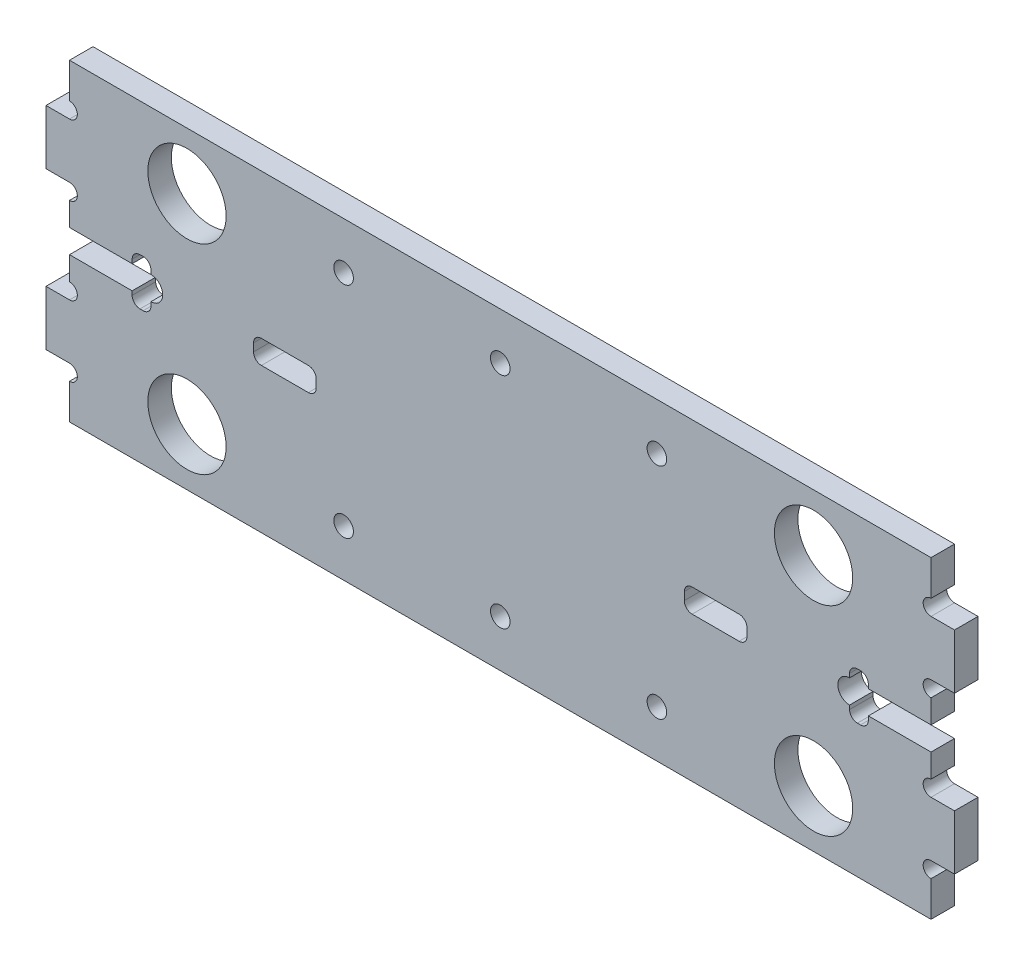
SolidWorks part; units mm, degrees
material "Acrylic (Medium-high impact)"
ref_plane "Front Plane" through (0, 0, 0) normal (0, 0, 1) x (1, 0, 0)
ref_plane "Top Plane" through (0, 0, 0) normal (0, 1, 0) x (1, 0, 0)
ref_plane "Right Plane" through (0, 0, 0) normal (1, 0, 0) x (0, 0, -1)
sketch "Sketch1" plane through (0, 0, 0) normal (0, 0, 1) x (1, 0, 0)
  line L0 (0, 20) -> (0, -20) construction
  line L1 (-55, 20) -> (55, 20)
  line L2 (-55, 20) -> (-55, -20)
  line L3 (-55, -20) -> (55, -20)
  line L4 (55, 20) -> (55, -20)
  line L5 (55, 0) -> (-55, 0) construction
  point P8 (0, 0)
extrude "Boss-Extrude1" add sketch "Sketch1" along normal blind 3
sketch "Sketch2" plane through (0, 0, 3) normal (0, 0, 1) x (1, 0, 0)
  line L0 (-55, 0) -> (55, 0) construction
  line L1 (-55, 20) -> (-55, -20) construction
  line L2 (55, -20) -> (55, 20) construction
  line L3 (55, 0) -> (55, -20) construction
  line L4 (55, 0) -> (55, 20) construction
  line L5 (55, 20) -> (58, 20) construction
  line L6 (58, 20) -> (58, -20) construction
  line L7 (58, -20) -> (55, -20) construction
  line L8 (0, 20) -> (0, -20) construction
  line L9 (55, 20) -> (-55, 20) construction
  line L10 (-55, -20) -> (55, -20) construction
  line L11 (55, -10) -> (58, -10) construction
  line L12 (55, 10) -> (58, 10) construction
  line L13 (58, 10) -> (58, 13.5)
  line L14 (58, 10) -> (58, 6.5)
  line L15 (58, 6.5) -> (55, 6.5)
  line L16 (55, 6.5) -> (55, 13.5)
  line L17 (55, 13.5) -> (58, 13.5)
  line L18 (55, -10) -> (55, -6.5)
  line L19 (55, -6.5) -> (58, -6.5)
  line L20 (58, -6.5) -> (58, -13.5)
  line L21 (58, -13.5) -> (55, -13.5)
  line L22 (55, -13.5) -> (55, -10)
  line L23 (-55, 6.5) -> (-55, 13.5)
  line L24 (-55, -13.5) -> (-55, -10)
  line L25 (-55, -10) -> (-55, -6.5)
  line L26 (-55, 10) -> (-58, 10) construction
  line L27 (-55, -10) -> (-58, -10) construction
  line L28 (-58, -20) -> (-55, -20) construction
  line L29 (-58, 20) -> (-58, -20) construction
  line L30 (-55, 20) -> (-58, 20) construction
  line L31 (-58, -13.5) -> (-55, -13.5)
  line L32 (-58, -6.5) -> (-58, -13.5)
  line L33 (-55, -6.5) -> (-58, -6.5)
  line L34 (-55, 13.5) -> (-58, 13.5)
  line L35 (-58, 6.5) -> (-55, 6.5)
  line L36 (-58, 10) -> (-58, 6.5)
  line L37 (-58, 10) -> (-58, 13.5)
extrude "Boss-Extrude2" add sketch "Sketch2" against normal blind 3
sketch "Sketch3" plane through (0, 0, 3) normal (0, 0, 1) x (1, 0, 0)
  line L0 (-55, 0) -> (55, 0) construction
  line L1 (-55, 6.5) -> (-55, -6.5) construction
  line L2 (55, -6.5) -> (55, 6.5) construction
  line L3 (-55, 13.5) -> (-55, 14.5) construction
  line L4 (-55, 20) -> (-55, 13.5) construction
  line L5 (-55, 14.5) -> (55, 14.5) construction
  line L6 (55, 13.5) -> (55, 20) construction
  line L7 (55, 14.5) -> (55, 5.5) construction
  line L8 (55, 5.5) -> (-55, 5.5) construction
  line L9 (-55, -6.5) -> (-55, -5.5) construction
  line L10 (-55, -5.5) -> (55, -5.5) construction
  line L11 (55, -5.5) -> (55, -14.5) construction
  line L12 (55, -20) -> (55, -13.5) construction
  line L13 (55, -14.5) -> (-55, -14.5) construction
  line L14 (-55, -13.5) -> (-55, -20) construction
  circle A1 centre (-55, 14.5) radius 1
  circle A2 centre (-55, 5.5) radius 1
  circle A3 centre (-55, -5.5) radius 1
  circle A4 centre (-55, -14.5) radius 1
  circle A5 centre (55, 14.5) radius 1
  circle A6 centre (55, 5.5) radius 1
  circle A7 centre (55, -5.5) radius 1
  circle A8 centre (55, -14.5) radius 1
extrude "Cut-Extrude1" cut sketch "Sketch3" against normal blind 3
sketch "Sketch4" plane through (0, 0, 3) normal (0, 0, 1) x (1, 0, 0)
  line L0 (-55, 0) -> (55, 0) construction
  line L1 (-55, 4.5) -> (-55, -4.5) construction
  line L2 (55, -4.5) -> (55, 4.5) construction
  line L3 (55, 0) -> (55, -1.5) construction
  line L4 (55, -1.5) -> (-55, -1.5) construction
  line L5 (-55, -1.5) -> (-55, 1.5) construction
  line L6 (-55, 1.5) -> (55, 1.5) construction
  line L7 (55, 1.5) -> (47, 1.5) construction
  line L8 (47, 20) -> (47, -20) construction
  line L9 (55, 20) -> (-55, 20) construction
  line L10 (-55, -20) -> (55, -20) construction
  line L11 (-55, 1.5) -> (-47, 1.5) construction
  line L12 (-47, 20) -> (-47, -20) construction
  line L13 (-47, 20) -> (-44.6, 20) construction
  line L14 (-44.6, 20) -> (-44.6, -20) construction
  line L15 (47, 20) -> (44.6, 20) construction
  line L16 (44.6, 20) -> (44.6, -20) construction
  line L17 (55, 1.5) -> (55, 3) construction
  line L18 (55, 3) -> (-55, 3) construction
  line L19 (-55, 3) -> (-55, -3) construction
  line L20 (-55, -3) -> (55, -3) construction
  line L21 (-44.6, 0) -> (-43.1, 0) construction
  line L22 (44.6, 0) -> (43.1, 0) construction
  line L24 (-55, 1.5) -> (-47, 1.5)
  line L25 (-55, 1.5) -> (-55, -1.5)
  line L26 (-55, -1.5) -> (-47, -1.5)
  line L27 (-47, 1.5) -> (-47, -1.5)
  line L28 (-47, 3) -> (-44.6, 3)
  line L29 (-47, 3) -> (-47, -3)
  line L30 (-47, -3) -> (-44.6, -3)
  line L31 (-44.6, 3) -> (-44.6, -3)
  line L32 (44.6, 3) -> (47, 3)
  line L33 (44.6, 3) -> (44.6, -3)
  line L34 (44.6, -3) -> (47, -3)
  line L35 (47, 3) -> (47, -3)
  line L36 (47, 1.5) -> (55, 1.5)
  line L37 (47, 1.5) -> (47, -1.5)
  line L38 (47, -1.5) -> (55, -1.5)
  line L39 (55, 1.5) -> (55, -1.5)
  arc A0 (44.6, 1.5) -> (44.6, -1.5) centre (44.6, 0) ccw
  arc A1 (-44.6, 1.5) -> (-44.6, -1.5) centre (-44.6, 0) cw
  line M10 (-55, 4.5) -> (-55, -4.5)
  line M24 (55, -4.5) -> (55, 4.5)
extrude "Cut-Extrude2" cut sketch "Sketch4" against normal blind 3 contours L27 L24 L26 M10 | L31 L28 L29 L27 L30 | A1 L31 | L35 L32 L33 L34 | L33 A0 | L35 L38 L36 M24
fillet "Fillet6" radius 1 8 edges at (-44.6, 3, 1.5) (-47, 3, 1.5) (-44.6, -3, 1.5) (-47, -3, 1.5) (47, 3, 1.5) (44.6, 3, 1.5) (47, -3, 1.5) (44.6, -3, 1.5)
sketch "Sketch5" plane through (0, 0, 3) normal (0, 0, 1) x (1, 0, 0)
  line L0 (-55, -1.5) -> (-55, 1.5) construction
  line L1 (55, -1.5) -> (55, 1.5) construction
  line L2 (-55, 0) -> (0, 0) construction
  line L3 (0, 0) -> (55, 0) construction
  line L4 (-27.5, 0) -> (-27.5, 1.5) construction
  line L5 (-27.5, 1.5) -> (-23.5, 1.5) construction
  line L6 (-23.5, 1.5) -> (-23.5, -1.5) construction
  line L7 (-23.5, -1.5) -> (-31.5, -1.5) construction
  line L8 (-31.5, -1.5) -> (-31.5, 1.5) construction
  line L9 (-31.5, 1.5) -> (-27.5, 1.5) construction
  line L10 (27.5, 0) -> (27.5, 1.5) construction
  line L11 (27.5, 1.5) -> (31.5, 1.5) construction
  line L12 (31.5, 1.5) -> (31.5, -1.5) construction
  line L13 (31.5, -1.5) -> (23.5, -1.5) construction
  line L14 (23.5, -1.5) -> (23.5, 1.5) construction
  line L15 (23.5, 1.5) -> (27.5, 1.5) construction
  line L17 (-31.5, 1.5) -> (-23.5, 1.5)
  line L18 (-31.5, 1.5) -> (-31.5, -1.5)
  line L19 (-31.5, -1.5) -> (-23.5, -1.5)
  line L20 (-23.5, 1.5) -> (-23.5, -1.5)
  line L21 (23.5, 1.5) -> (31.5, 1.5)
  line L22 (23.5, 1.5) -> (23.5, -1.5)
  line L23 (23.5, -1.5) -> (31.5, -1.5)
  line L24 (31.5, 1.5) -> (31.5, -1.5)
extrude "Cut-Extrude3" cut sketch "Sketch5" against normal blind 10
fillet "Fillet7" radius 1 8 edges at (-31.5, -1.5, 1.5) (-31.5, 1.5, 1.5) (-23.5, 1.5, 1.5) (23.5, -1.5, 1.5) (23.5, 1.5, 1.5) (31.5, 1.5, 1.5) (31.5, -1.5, 1.5) (-23.5, -1.5, 1.5)
sketch "Sketch6" plane through (0, 0, 3) normal (0, 0, 1) x (1, 0, 0)
  line L0 (0, 0) -> (0, 20) construction
  line L1 (55, 20) -> (-55, 20) construction
  line L2 (0, 20) -> (0, 14) construction
  line L3 (0, 0) -> (0, -20) construction
  line L4 (-55, -20) -> (55, -20) construction
  line L5 (0, -20) -> (0, -14) construction
  circle A0 centre (0, 14) radius 1.25
  circle A1 centre (0, -14) radius 1.25
  circle A2 centre (20, -14) radius 1.25
  circle A3 centre (20, 14) radius 1.25
  circle A4 centre (40, -14) radius 1.25
  circle A5 centre (40, 14) radius 1.25
  circle A6 centre (-20, -14) radius 1.25
  circle A7 centre (-20, 14) radius 1.25
  circle A8 centre (-40, -14) radius 1.25
  circle A9 centre (-40, 14) radius 1.25
  dimension "D1" = 3
  dimension "D2" = 3
extrude "Cut-Extrude4" cut sketch "Sketch6" against normal through all contours A8 | A6 | A1 | A2 | A4 | A5 | A3 | A0 | A7 | A9
sketch "Sketch7" plane through (0, 0, 3) normal (0, 0, 1) x (1, 0, 0)
  circle A0 centre (-40, 12.75) radius 5
  circle A1 centre (-40, 14) radius 1.25 construction
  circle A2 centre (-40, -12.75) radius 5
  circle A3 centre (-40, -14) radius 1.25 construction
  circle A4 centre (40, 12.75) radius 5
  circle A5 centre (40, 14) radius 1.25 construction
  circle A6 centre (40, -12.75) radius 5
  circle A7 centre (40, -14) radius 1.25 construction
extrude "Cut-Extrude5" cut sketch "Sketch7" against normal blind 10
